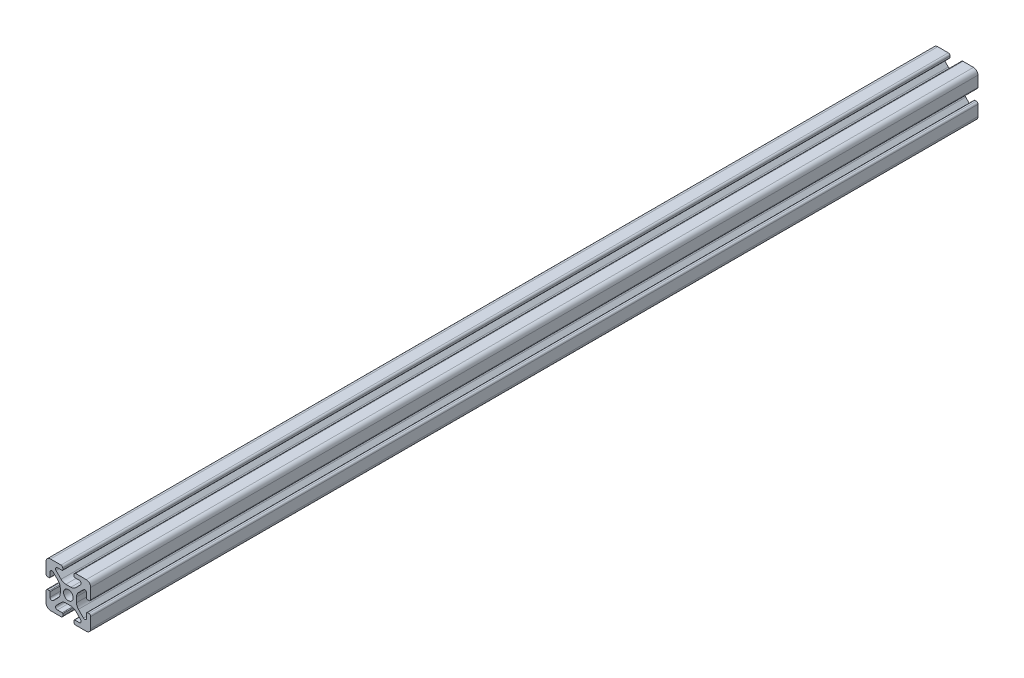
SolidWorks part; units mm, degrees
ref_plane "Front Plane" through (0, 0, 0) normal (0, 0, 1) x (1, 0, 0)
ref_plane "Top Plane" through (0, 0, 0) normal (0, 1, 0) x (1, 0, 0)
ref_plane "Right Plane" through (0, 0, 0) normal (1, 0, 0) x (0, 0, -1)
sketch "Sketch1" plane through (0, 0, 0) normal (0, 0, 1) x (1, 0, 0)
  line L2 (-9.9949, 7.9883) -> (-9.9949, 3.2893)
  line L3 (-7.9883, 9.9949) -> (-3.2893, 9.9949)
  line L4 (-2.5019, 9.2075) -> (-2.5019, 8.4963)
  line L5 (-2.8067, 8.1915) -> (-4.9149, 8.1915)
  line L6 (-5.5076, 6.7606) -> (-3.2528, 4.5058)
  line L7 (-6.7606, 5.5076) -> (-4.5058, 3.2528)
  line L8 (-8.1915, 4.9149) -> (-8.1915, 2.8067)
  line L9 (-8.4963, 2.5019) -> (-9.2075, 2.5019)
  line L11 (-1.1334, 3.6279) -> (1.1334, 3.6279)
  line L12 (-3.6279, 1.1334) -> (-3.6279, -1.1334)
  line L13 (8.4963, 2.5019) -> (9.2075, 2.5019)
  line L14 (8.1915, 4.9149) -> (8.1915, 2.8067)
  line L15 (9.9949, 7.9883) -> (9.9949, 3.2893)
  line L16 (7.9883, 9.9949) -> (3.2893, 9.9949)
  line L17 (2.5019, 9.2075) -> (2.5019, 8.4963)
  line L18 (2.8067, 8.1915) -> (4.9149, 8.1915)
  line L19 (3.6279, 1.1334) -> (3.6279, -1.1334)
  line L20 (5.5076, 6.7606) -> (3.2528, 4.5058)
  line L21 (6.7606, 5.5076) -> (4.5058, 3.2528)
  line L22 (-8.4963, -2.5019) -> (-9.2075, -2.5019)
  line L23 (-8.1915, -4.9149) -> (-8.1915, -2.8067)
  line L24 (-6.7606, -5.5076) -> (-4.5058, -3.2528)
  line L25 (-5.5076, -6.7606) -> (-3.2528, -4.5058)
  line L26 (-2.8067, -8.1915) -> (-4.9149, -8.1915)
  line L27 (-2.5019, -9.2075) -> (-2.5019, -8.4963)
  line L28 (-7.9883, -9.9949) -> (-3.2893, -9.9949)
  line L29 (-9.9949, -7.9883) -> (-9.9949, -3.2893)
  line L30 (9.9949, -7.9883) -> (9.9949, -3.2893)
  line L31 (7.9883, -9.9949) -> (3.2893, -9.9949)
  line L32 (2.5019, -9.2075) -> (2.5019, -8.4963)
  line L33 (2.8067, -8.1915) -> (4.9149, -8.1915)
  line L34 (5.5076, -6.7606) -> (3.2528, -4.5058)
  line L35 (6.7606, -5.5076) -> (4.5058, -3.2528)
  line L36 (8.1915, -4.9149) -> (8.1915, -2.8067)
  line L37 (8.4963, -2.5019) -> (9.2075, -2.5019)
  line L38 (-1.1334, -3.6279) -> (1.1334, -3.6279)
  circle A0 centre (0, 0) radius 2.1463
  arc A1 (-9.9949, 7.9883) -> (-7.9883, 9.9949) centre (-7.9883, 7.9883) cw
  arc A2 (-6.7606, 5.5076) -> (-8.1915, 4.9149) centre (-7.3533, 4.9149) ccw
  arc A3 (-4.9149, 8.1915) -> (-5.5076, 6.7606) centre (-4.9149, 7.3533) ccw
  arc A4 (-3.2893, 9.9949) -> (-2.5019, 9.2075) centre (-3.2893, 9.2075) cw
  arc A5 (-9.9949, 3.2893) -> (-9.2075, 2.5019) centre (-9.2075, 3.2893) ccw
  arc A6 (-8.1915, 2.8067) -> (-8.4963, 2.5019) centre (-8.4963, 2.8067) cw
  arc A7 (-2.5019, 8.4963) -> (-2.8067, 8.1915) centre (-2.8067, 8.4963) cw
  arc A8 (-1.1334, 3.6279) -> (-3.2528, 4.5058) centre (-1.1334, 6.6251) cw
  arc A9 (-3.6279, 1.1334) -> (-4.5058, 3.2528) centre (-6.6251, 1.1334) ccw
  arc A10 (8.1915, 2.8067) -> (8.4963, 2.5019) centre (8.4963, 2.8067) ccw
  arc A11 (9.9949, 3.2893) -> (9.2075, 2.5019) centre (9.2075, 3.2893) cw
  arc A12 (9.9949, 7.9883) -> (7.9883, 9.9949) centre (7.9883, 7.9883) ccw
  arc A13 (3.2893, 9.9949) -> (2.5019, 9.2075) centre (3.2893, 9.2075) ccw
  arc A14 (2.5019, 8.4963) -> (2.8067, 8.1915) centre (2.8067, 8.4963) ccw
  arc A15 (1.1334, 3.6279) -> (3.2528, 4.5058) centre (1.1334, 6.6251) ccw
  arc A16 (3.6279, 1.1334) -> (4.5058, 3.2528) centre (6.6251, 1.1334) cw
  arc A17 (6.7606, 5.5076) -> (8.1915, 4.9149) centre (7.3533, 4.9149) cw
  arc A18 (4.9149, 8.1915) -> (5.5076, 6.7606) centre (4.9149, 7.3533) cw
  arc A19 (-3.6279, -1.1334) -> (-4.5058, -3.2528) centre (-6.6251, -1.1334) cw
  arc A20 (-1.1334, -3.6279) -> (-3.2528, -4.5058) centre (-1.1334, -6.6251) ccw
  arc A21 (-2.5019, -8.4963) -> (-2.8067, -8.1915) centre (-2.8067, -8.4963) ccw
  arc A22 (-8.1915, -2.8067) -> (-8.4963, -2.5019) centre (-8.4963, -2.8067) ccw
  arc A23 (-9.9949, -3.2893) -> (-9.2075, -2.5019) centre (-9.2075, -3.2893) cw
  arc A24 (-3.2893, -9.9949) -> (-2.5019, -9.2075) centre (-3.2893, -9.2075) ccw
  arc A25 (-4.9149, -8.1915) -> (-5.5076, -6.7606) centre (-4.9149, -7.3533) cw
  arc A26 (-6.7606, -5.5076) -> (-8.1915, -4.9149) centre (-7.3533, -4.9149) cw
  arc A27 (-9.9949, -7.9883) -> (-7.9883, -9.9949) centre (-7.9883, -7.9883) ccw
  arc A28 (9.9949, -7.9883) -> (7.9883, -9.9949) centre (7.9883, -7.9883) cw
  arc A29 (6.7606, -5.5076) -> (8.1915, -4.9149) centre (7.3533, -4.9149) ccw
  arc A30 (4.9149, -8.1915) -> (5.5076, -6.7606) centre (4.9149, -7.3533) ccw
  arc A31 (3.2893, -9.9949) -> (2.5019, -9.2075) centre (3.2893, -9.2075) cw
  arc A32 (9.9949, -3.2893) -> (9.2075, -2.5019) centre (9.2075, -3.2893) ccw
  arc A33 (8.1915, -2.8067) -> (8.4963, -2.5019) centre (8.4963, -2.8067) cw
  arc A34 (2.5019, -8.4963) -> (2.8067, -8.1915) centre (2.8067, -8.4963) cw
  arc A35 (1.1334, -3.6279) -> (3.2528, -4.5058) centre (1.1334, -6.6251) cw
  arc A36 (3.6279, -1.1334) -> (4.5058, -3.2528) centre (6.6251, -1.1334) ccw
extrude "Boss-Extrude1" add sketch "Sketch1" along normal mid plane 396.3822
